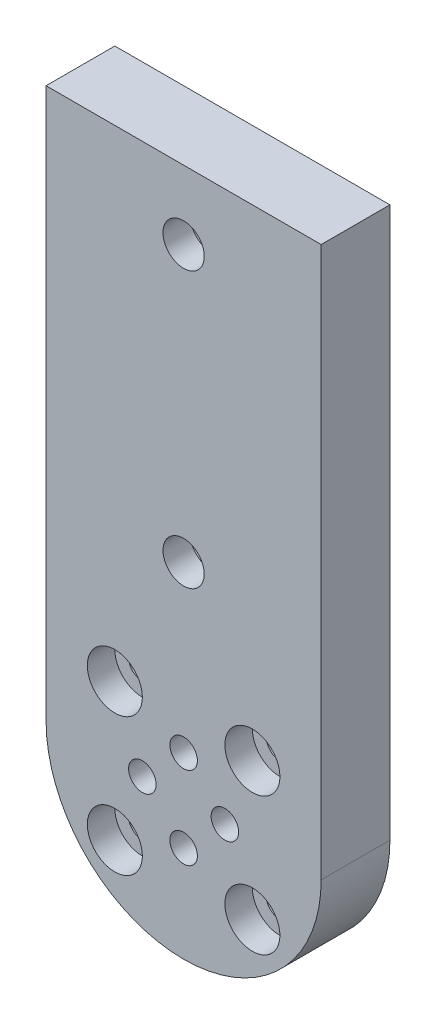
SolidWorks part; units mm, degrees
ref_plane "Front Plane" through (0, 0, 0) normal (0, 0, 1) x (1, 0, 0)
ref_plane "Top Plane" through (0, 0, 0) normal (0, 1, 0) x (1, 0, 0)
ref_plane "Right Plane" through (0, 0, 0) normal (1, 0, 0) x (0, 0, -1)
sketch "Sketch2" plane through (0, 0, 0) normal (0, 0, 1) x (1, 0, 0)
  line L0 (-10, 0) -> (-10, 40)
  line L1 (-5, 5) -> (5, 5) construction
  line L2 (-5, 5) -> (-5, -5) construction
  line L3 (-5, -5) -> (5, -5) construction
  line L4 (5, 5) -> (5, -5) construction
  line L5 (-5, 5) -> (5, -5) construction
  line L6 (-5, -5) -> (5, 5) construction
  line L7 (10, 0) -> (10, 40)
  line L8 (-10, 40) -> (10, 40)
  line L9 (0, 40) -> (0, -10) construction
  circle A0 centre (0, 0) radius 10
  circle A1 centre (-5, 5) radius 1
  circle A2 centre (5, 5) radius 1
  circle A3 centre (-5, -5) radius 1
  circle A4 centre (5, -5) radius 1
  circle A5 centre (0, 35) radius 1.5
  circle A6 centre (0, 15) radius 1.5
  point P19 (0, 35)
  dimension "D4" = 2
  dimension "D5" = 2
  dimension "D6" = 2
  dimension "D7" = 2
  dimension "D9" = 3
  dimension "D10" = 3
  dimension "D13" = 20
  dimension "D2" = 10
  dimension "D3" = 10
  dimension "D8" = 40
  dimension "D11" = 20
  dimension "D12" = 5
extrude "Boss-Extrude1" add sketch "Sketch2" along normal blind 5 contours A6 A0 A4 A3 A2 A1 | A6 A0 L7 L8 L0 A5
sketch "Sketch5" plane through (0, 0, 5) normal (0, 0, 1) x (1, 0, 0)
  line L0 (-10, 0) -> (10, 0) construction
  line L1 (0, -13.5) -> (0, 13.5) construction
  circle A0 centre (-5, 5) radius 2
  circle A1 centre (5, 5) radius 2
  circle A2 centre (5, -5) radius 2
  circle A3 centre (-5, -5) radius 2
  circle A4 centre (0, 15) radius 1.5 construction
  circle A5 centre (0, 3) radius 1
  circle A6 centre (-3, 0) radius 1
  circle A7 centre (3, 0) radius 1
  circle A8 centre (0, -3) radius 1
  point P17 (0, 0)
  point P24 (0, 0)
  dimension "D1" = 4
  dimension "D2" = 4
  dimension "D3" = 4
  dimension "D4" = 4
  dimension "D5" = 2
  dimension "D10" = 2
  dimension "D11" = 2
  dimension "D12" = 2
  dimension "D6" = 3
  dimension "D7" = 3
  dimension "D8" = 3
  dimension "D9" = 3
extrude "Cut-Extrude2" cut sketch "Sketch5" against normal blind 2
sketch "Sketch6" plane through (0, 0, 0) normal (0, 0, -1) x (-1, 0, 0)
  line L0 (0, 40) -> (0, -10) construction
  circle A0 centre (0, 35) radius 3.5
  circle A1 centre (0, 15) radius 3.5
  dimension "D1" = 7
  dimension "D2" = 7
extrude "Cut-Extrude3" cut sketch "Sketch6" against normal blind 3
